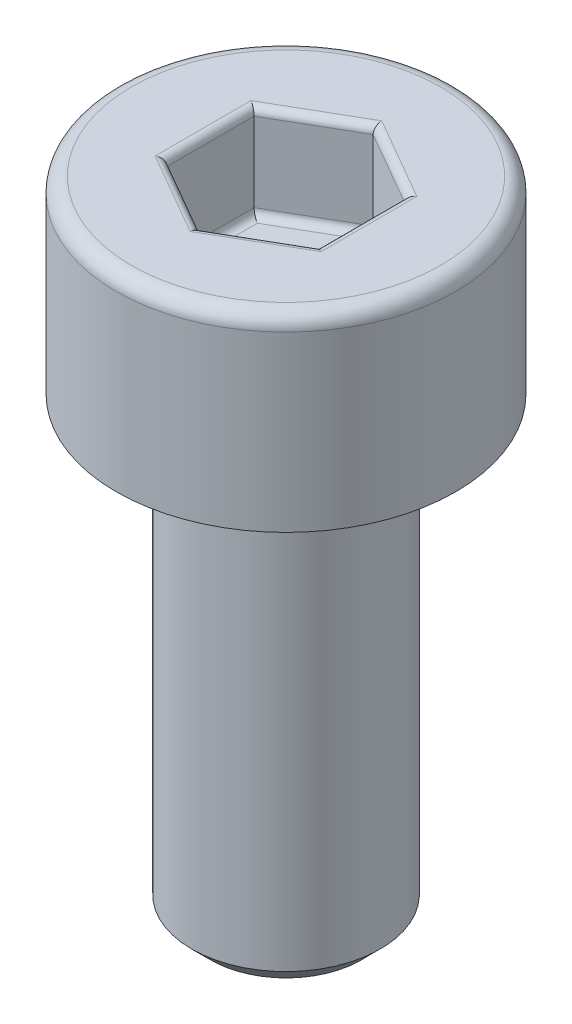
SolidWorks part; units mm, degrees
ref_plane "Front Plane" through (0, 0, 0) normal (0, 0, 1) x (1, 0, 0)
ref_plane "Top Plane" through (0, 0, 0) normal (0, 1, 0) x (1, 0, 0)
ref_plane "Right Plane" through (0, 0, 0) normal (1, 0, 0) x (0, 0, -1)
sketch "Sketch1" plane through (0, 0, 0) normal (0, 0, 1) x (1, 0, 0)
  line L0 (0, 0) -> (0, -47.0967) construction
  line L1 (0, -8.5) -> (-1.25, -8.5)
  line L2 (-1.25, -8.5) -> (-1.25, -2.5)
  line L3 (-1.25, -2.5) -> (-2.25, -2.5)
  line L4 (-2.25, -2.5) -> (-2.25, 0)
  line L5 (-2.25, 0) -> (0, 0)
  line L6 (0, 0) -> (0, -8.5)
  dimension "D1" = 6
  dimension "d" = 2.5
  dimension "k" = 2.5
  dimension "dk" = 4.5
revolve "Revolve1" add sketch "Sketch1" angle 360 about L0
chamfer "Chamfer1" distance 0.25 angle 45 2 edges at (0, -2.5, 1.25) (0, -8.5, 1.25)
fillet "Fillet1" radius 0.2 1 edges at (0, 0, 2.25)
sketch "Sketch2" plane through (0, 0, 0) normal (0, 1, 0) x (1, 0, 0)
  line L1 (0, 1.1547) -> (-1, 0.5774)
  line L2 (-1, 0.5774) -> (-1, -0.5774)
  line L3 (-1, -0.5774) -> (0, -1.1547)
  line L4 (0, -1.1547) -> (1, -0.5774)
  line L5 (1, -0.5774) -> (1, 0.5774)
  line L6 (1, 0.5774) -> (0, 1.1547)
  circle A0 centre (0, 0) radius 1 construction
  dimension "s" = 2
extrude "Cut-Extrude1" cut sketch "Sketch2" against normal blind 1.25
fillet "Fillet2" radius 0.1 12 edges at (-0.5, 0, -0.866) (-1, 0, 0) (-0.5, 0, 0.866) (0.5, 0, 0.866) (1, 0, 0) (0.5, 0, -0.866) (1, -1.25, 0) (0.5, -1.25, 0.866) (-0.5, -1.25, 0.866) (-1, -1.25, 0) (-0.5, -1.25, -0.866) (0.5, -1.25, -0.866)
